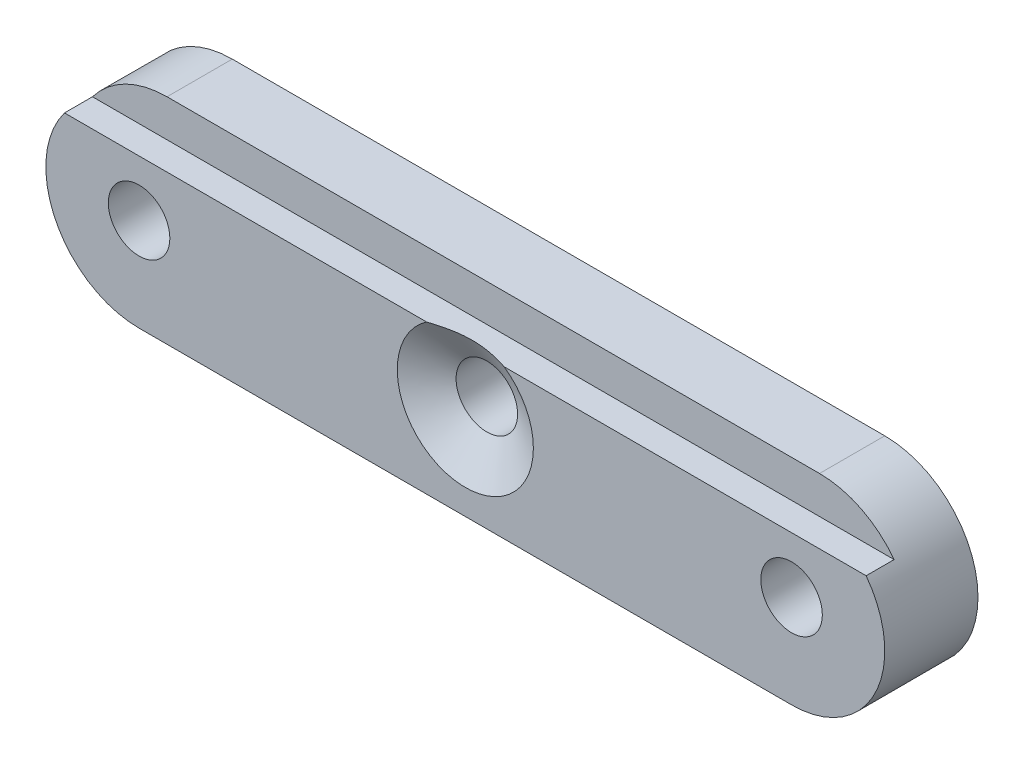
SolidWorks part; units mm, degrees
ref_plane "Front Plane" through (0, 0, 0) normal (0, 0, 1) x (1, 0, 0)
ref_plane "Top Plane" through (0, 0, 0) normal (0, 1, 0) x (1, 0, 0)
ref_plane "Right Plane" through (0, 0, 0) normal (1, 0, 0) x (0, 0, -1)
sketch "Sketch1" plane through (0, 0, 0) normal (0, 0, 1) x (1, 0, 0)
  line L0 (0, 0) -> (35, 0) construction
  line L1 (0, 5) -> (35, 5)
  line L2 (0, -5) -> (35, -5)
  arc A0 (0, 5) -> (0, -5) centre (0, 0) ccw
  arc A1 (35, -5) -> (35, 5) centre (35, 0) ccw
  circle A2 centre (35, 0) radius 1.65
  circle A3 centre (0, 0) radius 1.65
  point P3 (17.5, 0)
  dimension "D2" = 5
  dimension "D3" = 3.3
  dimension "D1" = 35
extrude "Boss-Extrude1" add sketch "Sketch1" along normal blind 5
sketch "Sketch2" plane through (0, 0, 5) normal (0, 0, 1) x (1, 0, 0)
  line L0 (0, -5) -> (35, -5) construction
  circle A0 centre (17.5, 0) radius 1.65
  circle A1 centre (35, 0) radius 1.65 construction
  dimension "D1" = 3.3
  dimension "D2" = 5
  dimension "D3" = 17.5
extrude "Cut-Extrude1" cut sketch "Sketch2" against normal blind 5
chamfer "Chamfer1" distance 2 angle 30 1 edges at (19.15, 0, 5)
sketch "Sketch3" plane through (0, 0, 0) normal (1, 0, 0) x (0, 0, -1)
  line L1 (-5, 3) -> (-3.5, 3)
  line L2 (-5, 3) -> (-5, 5)
  line L3 (-5, 5) -> (-3.5, 5)
  line L4 (-3.5, 3) -> (-3.5, 5)
  point P5 (0, 0)
  point P6 (0, 0)
  dimension "D1" = 2
  dimension "D2" = 1.5
extrude "Cut-Extrude2" cut sketch "Sketch3" along normal mid plane 95
